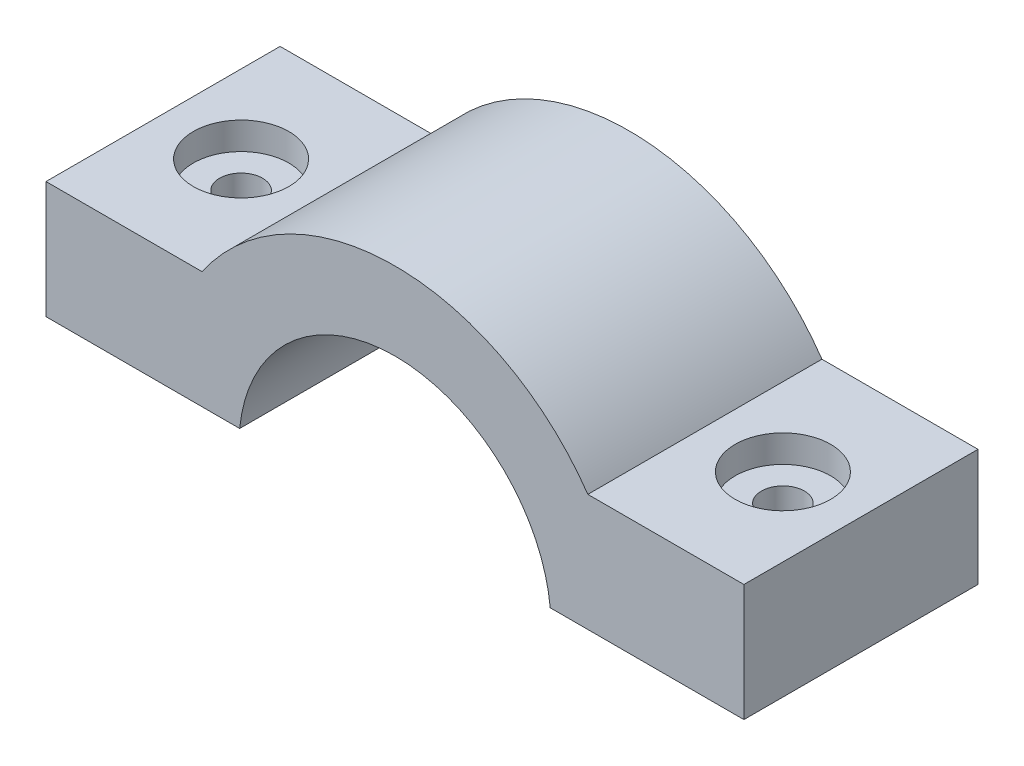
SolidWorks part; units mm, degrees
ref_plane "Plan de face" through (0, 0, 0) normal (0, 0, 1) x (1, 0, 0)
ref_plane "Plan de dessus" through (0, 0, 0) normal (0, 1, 0) x (1, 0, 0)
ref_plane "Plan de droite" through (0, 0, 0) normal (1, 0, 0) x (0, 0, -1)
sketch "Esquisse1" plane through (0, 0, 0) normal (0, 0, 1) x (1, 0, 0)
  line L0 (42.6647, -2.0708) -> (67.4834, -2.0708)
  line L1 (107.2829, -2.0708) -> (132.1015, -2.0708)
  line L2 (132.1015, -2.0708) -> (132.1015, 12.9292)
  line L3 (132.1015, 12.9292) -> (112.1015, 12.9292)
  line L4 (42.6647, -2.0708) -> (42.6647, 12.9292)
  line L5 (42.6647, 12.9292) -> (62.6647, 12.9292)
  circle A0 centre (87.3831, -4.0708) radius 20 construction
  arc A1 (67.4834, -2.0708) -> (107.2829, -2.0708) centre (87.3831, -4.0708) cw
  arc A2 (62.6647, 12.9292) -> (112.1015, 12.9292) centre (87.3831, -4.0708) cw
  dimension "D1" = 10
  dimension "D2" = 15
  dimension "D3" = 20
  dimension "D4" = 20
  dimension "D5" = 2
extrude "Boss.-Extru.1" add sketch "Esquisse1" along normal mid plane 30 contours A2 L3 L2 L1 A1 L0 L4 L5
hole_wizard "Chambrage pour vis à tête hexagonale M51" positions "Esquisse3D1" profile "Esquisse2" counterbore size "M5" standard "ISO" end condition through all
sketch3d "Esquisse3D1"
  line L0 (42.6647, 12.9292, -15) -> (62.6647, 12.9292, 15) construction
  line L2 (112.1015, 12.9292, -15) -> (132.1015, 12.9292, 15) construction
  point P0 (52.6647, 12.9292, 0)
  point P2 (122.1015, 12.9292, 0)
sketch "Esquisse2" plane through (52.6647, 12.9292, 0) normal (1, 0, 0) x (0, 0, 1)
  line L0 (0, 0) -> (0, 15)
  line L1 (0, 15) -> (2.75, 15)
  line L3 (2.75, 15) -> (2.75, 3.5)
  line L4 (2.75, 3.5) -> (6.119, 3.5)
  line L5 (6.119, 3.5) -> (6.119, 0)
  line L7 (6.119, 0) -> (0, 0)
  line L11 (0, -6.35) -> (0, 107.95) construction
  dimension "Diamètre du perçage jusqu'au prochain" = 5.5
  dimension "Profondeur du perçage jusqu'au prochain" = 15
  dimension "Diamètre du chambrage" = 12.238
  dimension "Profondeur du chambrage" = 3.5
